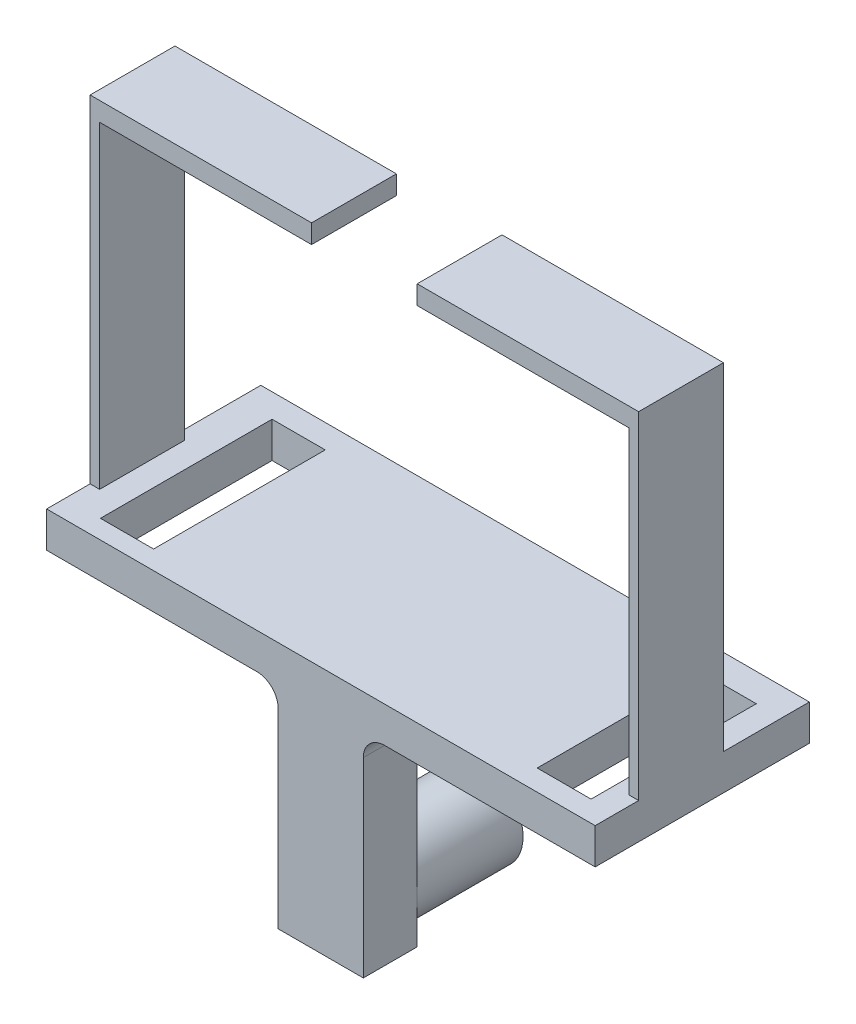
SolidWorks part; units mm, degrees
material "Ti-6Al-4V"
ref_plane "Front Plane" through (0, 0, 0) normal (0, 0, 1) x (1, 0, 0)
ref_plane "Top Plane" through (0, 0, 0) normal (0, 1, 0) x (1, 0, 0)
ref_plane "Right Plane" through (0, 0, 0) normal (1, 0, 0) x (0, 0, -1)
sketch "Sketch6" plane through (0, 0, 0) normal (0, 1, 0) x (1, 0, 0)
  line L1 (-17.2688, 14.0633) -> (-7.0707, 14.0633)
  line L2 (-17.2688, 14.0633) -> (-17.2688, 7.632)
  line L3 (-17.2688, 7.632) -> (-7.0707, 7.632)
  line L4 (-7.0707, 14.0633) -> (-7.0707, 7.632)
  dimension "D1" = 10.1981
  dimension "D2" = 6.4313
extrude "Boss-Extrude3" add sketch "Sketch6" along normal blind 25.4
sketch "Sketch8" plane through (0, 0, -14.0633) normal (0, 0, 1) x (1, 0, 0)
  line L1 (-7.0707, 0) -> (-17.2688, 0) construction
  line L6 (-17.2688, 10.1971) -> (-7.0707, 0) construction
  line L7 (-7.0707, 25.4) -> (-7.0707, 0) construction
  line L8 (-7.0707, 10.1971) -> (-17.2688, 10.1971) construction
  line L9 (-17.2688, 25.4) -> (-17.2688, 0) construction
  line L10 (-7.0707, 0) -> (-7.0707, 10.1971) construction
  line L11 (-7.0707, 10.1971) -> (-17.2688, 0) construction
  circle A0 centre (-12.1698, 5.0985) radius 5.0991
  dimension "D1" = 10.1981
extrude "Boss-Extrude5" add sketch "Sketch8" against normal blind 12.7
sketch "Sketch11" plane through (0, 25.4, 0) normal (0, 1, 0) x (1, 0, 0)
  line L0 (-17.2688, 7.632) -> (-7.0707, 7.632) construction
  line L2 (-40.8068, 30.4385) -> (-34.4388, 30.4385)
  line L3 (-44.998, 7.632) -> (20.6965, 7.632)
  line L4 (-44.998, 7.632) -> (-44.998, 33.286)
  line L5 (-44.998, 33.286) -> (20.6965, 33.286)
  line L6 (20.6965, 7.632) -> (20.6965, 33.286)
  line L7 (-40.8068, 30.4385) -> (-40.8068, 9.8813)
  line L8 (-40.8068, 9.8813) -> (-34.4388, 9.8813)
  line L9 (-34.4388, 30.4385) -> (-34.4388, 9.8813)
  line L10 (11.2485, 29.9256) -> (17.702, 29.9256)
  line L11 (11.2485, 29.9256) -> (11.2485, 10.1377)
  line L12 (11.2485, 10.1377) -> (17.702, 10.1377)
  line L13 (17.702, 29.9256) -> (17.702, 10.1377)
  dimension "D1" = 25.654
  dimension "D2" = 65.6946
extrude "Boss-Extrude10" add sketch "Sketch11" along normal blind 4.2875
sketch "Sketch16" plane through (0, 29.6875, 0) normal (0, 1, 0) x (1, 0, 0)
  line L3 (20.6965, 33.286) -> (20.6965, 7.632) construction
  line L4 (-44.998, 12.839) -> (-43.855, 12.839)
  line L7 (-44.998, 12.839) -> (-44.998, 22.999)
  line L8 (-44.998, 22.999) -> (-43.855, 22.999)
  line L9 (-43.855, 12.839) -> (-43.855, 22.999)
  line L10 (-44.998, 7.632) -> (20.6965, 7.632) construction
  line L11 (20.6965, 7.632) -> (20.6965, 33.286) construction
  line L13 (20.6965, 22.999) -> (19.5535, 22.999)
  line L14 (20.6965, 22.999) -> (20.6965, 12.839)
  line L15 (20.6965, 12.839) -> (19.5535, 12.839)
  line L16 (19.5535, 22.999) -> (19.5535, 12.839)
  dimension "D1" = 1.143
  dimension "D2" = 1.143
  dimension "D3" = 10.16
  dimension "D4" = 10.16
extrude "Boss-Extrude11" add sketch "Sketch16" along normal blind 38.0746
sketch "Sketch17" plane through (0, 67.7621, 0) normal (0, 1, 0) x (1, 0, 0)
  line L0 (-44.998, 22.999) -> (-18.4753, 22.999) construction
  line L1 (-44.998, 12.839) -> (-41.8446, 12.839) construction
  line L2 (20.6965, 22.999) -> (-5.8261, 22.999) construction
  line L3 (-44.998, 22.999) -> (-18.4753, 22.999)
  line L4 (-44.998, 22.999) -> (-44.998, 12.839)
  line L5 (-44.998, 12.839) -> (-18.4753, 12.839)
  line L6 (-18.4753, 22.999) -> (-18.4753, 12.839)
  line L7 (20.6965, 12.839) -> (3.53, 12.839) construction
  line L9 (20.6965, 12.839) -> (-5.8261, 12.839)
  line L10 (20.6965, 12.839) -> (20.6965, 22.999)
  line L11 (20.6965, 22.999) -> (-5.8261, 22.999)
  line L12 (-5.8261, 12.839) -> (-5.8261, 22.999)
  dimension "D1" = 26.5227
  dimension "D2" = 26.5227
extrude "Boss-Extrude12" add sketch "Sketch17" along normal blind 2.2606
ref_plane "Plane1" through (-7.0707, 25.4, -14.0633) normal (-1, 0, 0) x (0, 0, 1)
fillet "Fillet2" radius 2.54 1 edges at (-12.1698, 25.4, -14.0633)
fillet "Fillet3" radius 2.54 1 edges at (-17.2688, 25.4, -12.1177)
fillet "Fillet4" radius 2.54 1 edges at (-7.0707, 25.4, -12.1177)
sketch "Sketch19" plane through (0, 0, -26.7633) normal (0, 0, -1) x (-1, 0, 0)
  circle A0 centre (12.1698, 5.0985) radius 4.064
  dimension "D1" = 8.128
extrude "Cut-Extrude1" cut sketch "Sketch19" against normal blind 12.7
equation "\"baseH\"= 2.5864"
equation "\"baseD\"= 1.01"
equation "\"baseT\"= 0.1688"
equation "\"cylwallH\"= 1"
equation "\"cylwallD\"= 0.4015"
equation "\"cylwallT\"= 0.1688"
equation "\"cylH\"= 1'C"
equation "\"cylD\"= 0.40146"
equation "\"cylT\"= 0.75"
equation "\"sidewallH\"= 0.045"
equation "\"sidewallD\"= 0.2"
equation "\"sidewallT\"= 1.499"
equation "\"horizwallH\"= 0.9992"
equation "\"horizwallD\"= 0.2"
equation "\"horizwallT\"= 0.178"
equation "\"E\"= 16534303"
equation "\"SF\"= 4"
equation "\"W\"= 4 * \"lbs\""
equation "\"Ys\"= 119946"
equation "\"dMAX\"= 0.005"
equation "\"lbs\"= 508"
equation "\"z\"= \"SF\" * \"W\" * ( \"cylT\" / 2 * \"Ys\" )"
equation "\"r\"= ( 4 * ( \"z\" / pi ) ) ^ ( 1 / 3 )"
